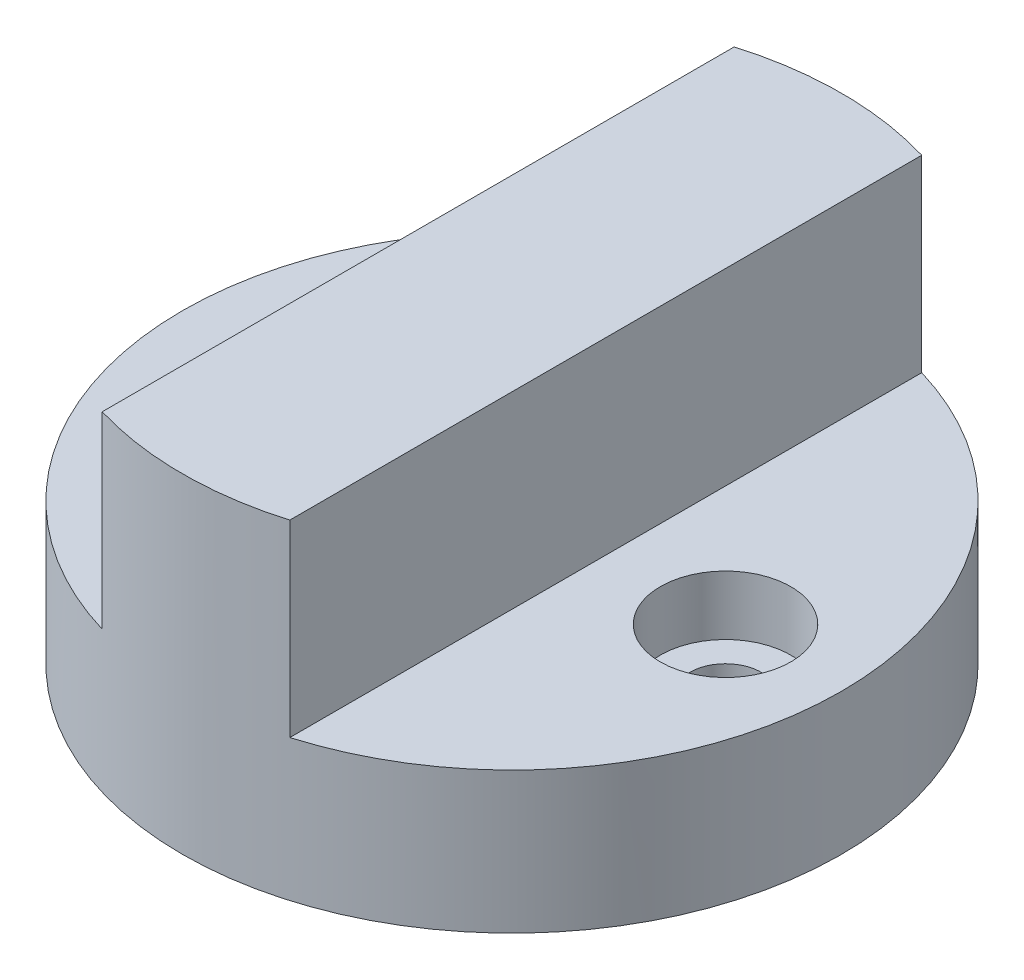
SolidWorks part; units mm, degrees
ref_plane "Front Plane" through (0, 0, 0) normal (0, 0, 1) x (1, 0, 0)
ref_plane "Top Plane" through (0, 0, 0) normal (0, 1, 0) x (1, 0, 0)
ref_plane "Right Plane" through (0, 0, 0) normal (1, 0, 0) x (0, 0, -1)
sketch "Sketch1" plane through (0, 0, 0) normal (0, 1, 0) x (1, 0, 0)
  circle A0 centre (0, 0) radius 11.1125
  dimension "D1" = 22.225
extrude "Boss-Extrude1" add sketch "Sketch1" along normal blind 11.1125
sketch "Sketch2" plane through (0, 11.1125, 0) normal (0, 1, 0) x (1, 0, 0)
  line L0 (0, 11.1125) -> (0, -11.1125) construction
  line L1 (-3.1623, 10.6531) -> (-3.1623, -10.6531)
  line L2 (3.1623, 10.6531) -> (3.1623, -10.6531)
  circle A0 centre (0, 0) radius 11.1125 construction
  arc A1 (-3.1623, 10.6531) -> (-3.1623, -10.6531) centre (0, 0) ccw
  arc A2 (3.1623, 10.6531) -> (3.1623, -10.6531) centre (0, 0) cw
  dimension "D1" = 6.3246
extrude "Cut-Extrude1" cut sketch "Sketch2" against normal blind 6.35
hole_wizard "CBORE for M2 SHCS1" positions "Sketch4" profile "Sketch5" counterbore size "M2" standard "ANSI Metric" end condition through all
sketch "Sketch4" plane through (0, 4.7625, 0) normal (0, 1, 0) x (1, 0, 0)
  line L4 (-7.2, 0) -> (0, 0) construction
  line L6 (0, 0) -> (0, 5.5182) construction
  point P0 (-7.2, 0)
  point P55 (7.2, 0)
  dimension "D1" = 7.2
sketch "Sketch5" plane through (-7.2, 4.7625, 0) normal (1, 0, 0) x (0, 0, 1)
  line L0 (0, 0) -> (0, 4.7625)
  line L1 (0, 4.7625) -> (1.2, 4.7625)
  line L3 (1.2, 4.7625) -> (1.2, 2)
  line L4 (1.2, 2) -> (2.2, 2)
  line L5 (2.2, 2) -> (2.2, 0)
  line L7 (2.2, 0) -> (0, 0)
  line L11 (0, -6.35) -> (0, 107.95) construction
  dimension "Thru Hole Dia." = 2.4
  dimension "Thru Hole Depth" = 4.7625
  dimension "C'Bore Dia." = 4.4
  dimension "C'Bore Depth" = 2
